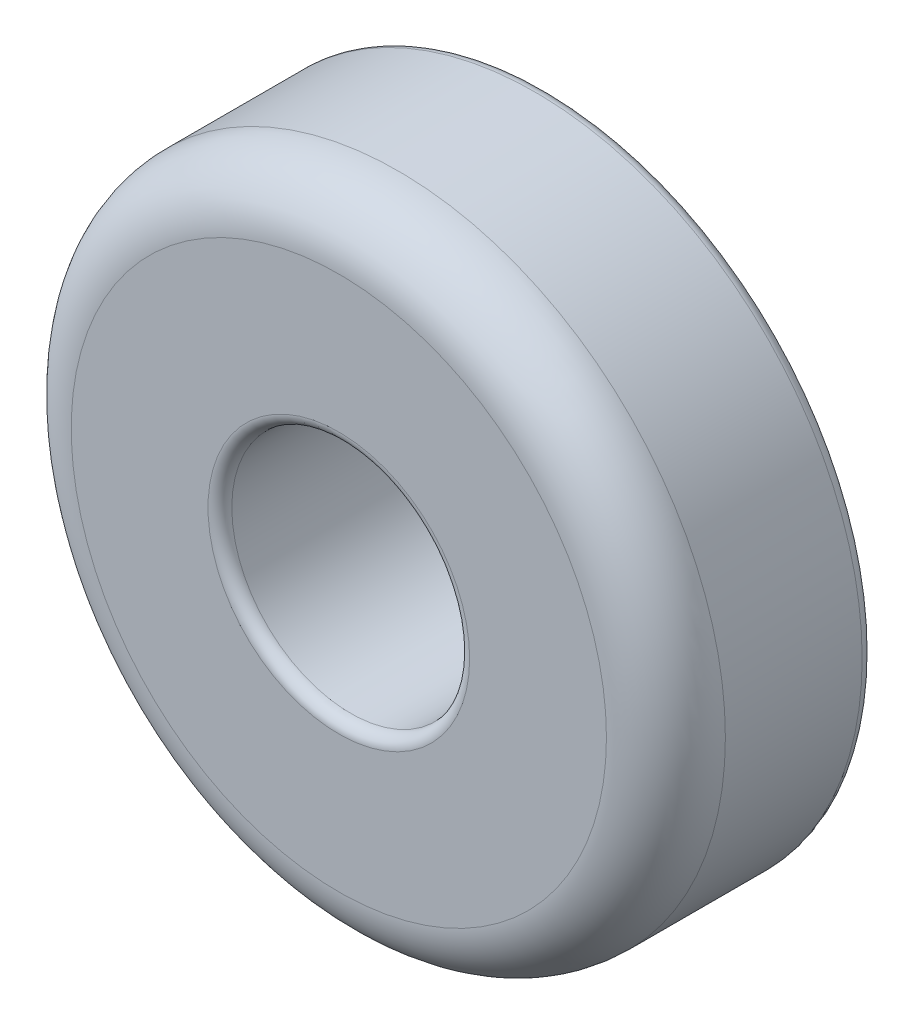
SolidWorks part; units mm, degrees
material "Copper"
ref_plane "Front Plane" through (0, 0, 0) normal (0, 0, 1) x (1, 0, 0)
ref_plane "Top Plane" through (0, 0, 0) normal (0, 1, 0) x (1, 0, 0)
ref_plane "Right Plane" through (0, 0, 0) normal (1, 0, 0) x (0, 0, -1)
sketch "Sketch1" plane through (0, 0, 0) normal (0, 0, 1) x (1, 0, 0)
  circle A0 centre (0, 0) radius 1
  dimension "D1" = 2
extrude "Extrude-Thin1" add sketch "Sketch1" along normal blind 1.75 thin
fillet "Fillet1" radius 0.5 1 edges at (2.75, 0, 1.75)
fillet "Fillet2" radius 0.1 3 edges at (1, 0, 0) (2.75, 0, 0) (1, 0, 1.75)
scale "Scale1" scale about centroid uniform scaling yes scale factor 0.445
